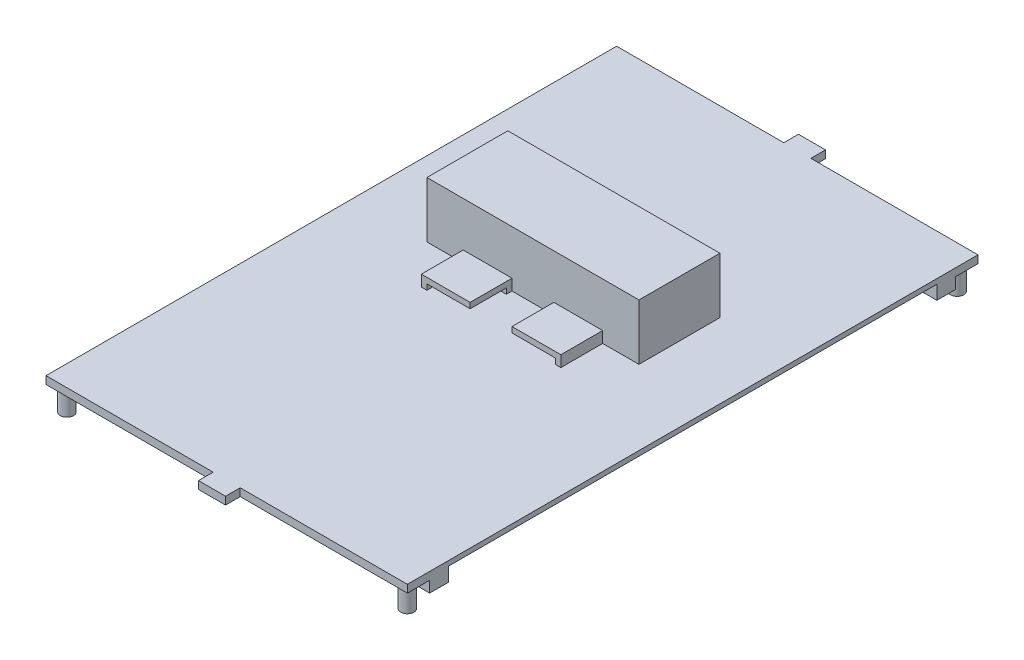
SolidWorks part; units mm, degrees
ref_plane "前视基准面" through (0, 0, 0) normal (0, 0, 1) x (1, 0, 0)
ref_plane "上视基准面" through (0, 0, 0) normal (0, 1, 0) x (1, 0, 0)
ref_plane "右视基准面" through (0, 0, 0) normal (1, 0, 0) x (0, 0, -1)
sketch "草图1" plane through (0, 0, 0) normal (0, 1, 0) x (1, 0, 0)
  line L1 (-64.75, 102.25) -> (64.75, 102.25)
  line L2 (-64.75, 102.25) -> (-64.75, -102.25)
  line L3 (-64.75, -102.25) -> (64.75, -102.25)
  line L4 (64.75, 102.25) -> (64.75, -102.25)
  line L5 (-64.75, 102.25) -> (64.75, -102.25) construction
  line L6 (-64.75, -102.25) -> (64.75, 102.25) construction
  point P0 (0, 0)
  dimension "D1" = 129.5
  dimension "D2" = 204.5
extrude "凸台-拉伸1" add sketch "草图1" along normal blind 6.75
sketch "草图2" plane through (0, 0, 0) normal (0, -1, 0) x (1, 0, 0)
  line L0 (-64.75, 102.25) -> (-64.75, 94.25)
  line L1 (-64.75, -102.25) -> (-64.75, 102.25) construction
  line L2 (-64.75, 94.25) -> (64.75, 94.25)
  line L3 (64.75, 102.25) -> (64.75, -102.25) construction
  line L4 (64.75, 94.25) -> (64.75, 102.25)
  line L5 (64.75, 102.25) -> (-64.75, 102.25)
  line L6 (-86.0384, 0) -> (144.5402, 0) construction
  line L7 (64.75, -102.25) -> (-64.75, -102.25)
  line L8 (64.75, -94.25) -> (64.75, -102.25)
  line L9 (-64.75, -94.25) -> (64.75, -94.25)
  line L10 (-64.75, -102.25) -> (-64.75, -94.25)
  dimension "D1" = 8
extrude "切除-拉伸1" cut sketch "草图2" against normal blind 4
sketch "草图3" plane through (0, 4, 0) normal (0, -1, 0) x (1, 0, 0)
  line L1 (-61, 98.5) -> (61, 98.5) construction
  line L2 (-61, 98.5) -> (-61, -98.5) construction
  line L3 (-61, -98.5) -> (61, -98.5) construction
  line L4 (61, 98.5) -> (61, -98.5) construction
  line L5 (-61, 98.5) -> (61, -98.5) construction
  line L6 (-61, -98.5) -> (61, 98.5) construction
  circle A0 centre (-61, 98.5) radius 2.35
  circle A1 centre (61, 98.5) radius 2.35
  circle A2 centre (61, -98.5) radius 2.35
  circle A3 centre (-61, -98.5) radius 2.35
  point P0 (0, 0)
  dimension "D3" = 4.7
  dimension "D1" = 197
  dimension "D2" = 122
extrude "凸台-拉伸2" add sketch "草图3" along normal blind 8.5
sketch "草图4" plane through (0, 0, 0) normal (0, -1, 0) x (1, 0, 0)
  line L0 (64.75, 87.5) -> (-55.25, 87.5)
  line L5 (64.75, 94.25) -> (64.75, -94.25) construction
  line L6 (-55.25, 87.5) -> (-55.25, -87.5)
  line L7 (-55.25, -87.5) -> (64.75, -87.5)
  line L8 (64.75, -87.5) -> (64.75, 87.5)
  point P7 (-55.25, 0)
  dimension "D1" = 120
  dimension "D2" = 175
extrude "切除-拉伸3" cut sketch "草图4" against normal blind 5
sketch "草图5" plane through (0, 6.75, 0) normal (0, 1, 0) x (1, 0, 0)
  line L1 (-4.85, 107.5) -> (4.85, 107.5)
  line L2 (-4.85, 107.5) -> (-4.85, -107.5)
  line L3 (-4.85, -107.5) -> (4.85, -107.5)
  line L4 (4.85, 107.5) -> (4.85, -107.5)
  line L5 (-4.85, 107.5) -> (4.85, -107.5) construction
  line L6 (-4.85, -107.5) -> (4.85, 107.5) construction
  point P0 (0, 0)
  dimension "D1" = 215
  dimension "D2" = 9.7
extrude "凸台-拉伸3" add sketch "草图5" against normal up to surface (2.75 mm away) up to face at (61, 4, 96.15)
sketch "草图6" plane through (0, 6.75, 0) normal (0, 1, 0) x (1, 0, 0)
  line L1 (-25, 7.5) -> (25, 7.5)
  line L2 (-25, 7.5) -> (-25, -7.5)
  line L3 (-25, -7.5) -> (25, -7.5)
  line L4 (25, 7.5) -> (25, -7.5)
  line L5 (-25, 7.5) -> (25, -7.5) construction
  line L6 (-25, -7.5) -> (25, 7.5) construction
  point P0 (0, 0)
  dimension "D1" = 50
  dimension "D2" = 15
extrude "凸台-拉伸4" add sketch "草图6" along normal blind 4
sketch "草图7" plane through (0, 0, 7.5) normal (0, 0, 1) x (1, 0, 0)
  line L0 (-23, 6.75) -> (-23, 8.75)
  line L1 (-25, 6.75) -> (25, 6.75) construction
  line L2 (-23, 8.75) -> (23, 8.75)
  line L3 (23, 8.75) -> (23, 6.75)
  line L4 (4.85, 6.75) -> (64.75, 6.75) construction
  line L5 (23, 6.75) -> (-23, 6.75)
  point P5 (0, 6.75)
  dimension "D1" = 46
  dimension "D2" = 2
extrude "切除-拉伸4" cut sketch "草图7" against normal blind 13
sketch "草图8" plane through (0, 10.75, 0) normal (0, 1, 0) x (1, 0, 0)
  line L0 (-25, -7.5) -> (25, -7.5) construction
  line L3 (-7.5, 7.5) -> (7.5, 7.5)
  line L4 (-7.5, 7.5) -> (-7.5, -7.5)
  line L5 (-7.5, -7.5) -> (7.5, -7.5)
  line L6 (7.5, 7.5) -> (7.5, -7.5)
  line L7 (-7.5, 7.5) -> (7.5, -7.5) construction
  line L8 (-7.5, -7.5) -> (7.5, 7.5) construction
  point P0 (0, 0)
  dimension "D1" = 15
extrude "切除-拉伸5" cut sketch "草图8" against normal blind 4
sketch "草图9" plane through (0, 6.75, 0) normal (0, 1, 0) x (1, 0, 0)
  line L0 (0, 100.8272) -> (0, -116.7088) construction
  line L1 (25, 7.5) -> (7.5, 7.5) construction
  line L2 (-38, 36.5) -> (38, 36.5)
  line L3 (-38, 36.5) -> (-38, 7.5)
  line L4 (-38, 7.5) -> (38, 7.5)
  line L5 (38, 36.5) -> (38, 7.5)
  line L6 (-38, 36.5) -> (38, 7.5) construction
  line L7 (-38, 7.5) -> (38, 36.5) construction
  point P3 (0, 22)
  dimension "D1" = 76
  dimension "D2" = 29
extrude "凸台-拉伸5" add sketch "草图9" along normal blind 20
sketch "草图10" plane through (0, 4, 0) normal (0, -1, 0) x (1, 0, 0)
  line L0 (-4.85, 87.5) -> (4.85, 87.5) construction
  line L1 (4.85, -87.5) -> (-4.85, -87.5)
  line L2 (4.85, -87.5) -> (4.85, 87.5)
  line L3 (4.85, 87.5) -> (-4.85, 87.5)
  line L4 (-4.85, -87.5) -> (-4.85, 87.5)
  line L5 (4.85, -87.5) -> (-4.85, 87.5) construction
  line L6 (4.85, 87.5) -> (-4.85, -87.5) construction
  line L7 (-4.85, -87.5) -> (-4.85, 87.5) construction
  point P0 (0, 0)
extrude "切除-拉伸6" cut sketch "草图10" against normal up to surface (1 mm away) up to face at (34.8, 5, 0)
sketch "草图11" plane through (0, 5, 0) normal (0, -1, 0) x (1, 0, 0)
  line L1 (-35.5, -9.25) -> (35.5, -9.25)
  line L2 (-35.5, -9.25) -> (-35.5, -34.75)
  line L3 (-35.5, -34.75) -> (35.5, -34.75)
  line L4 (35.5, -9.25) -> (35.5, -34.75)
  line L5 (-35.5, -9.25) -> (35.5, -34.75) construction
  line L6 (-35.5, -34.75) -> (35.5, -9.25) construction
  point P0 (0, 22.75)
  point P6 (0, -22)
  dimension "D1" = 71
  dimension "D2" = 25.5
  dimension "D3" = 22
extrude "切除-拉伸8" cut sketch "草图11" against normal blind 20.2
